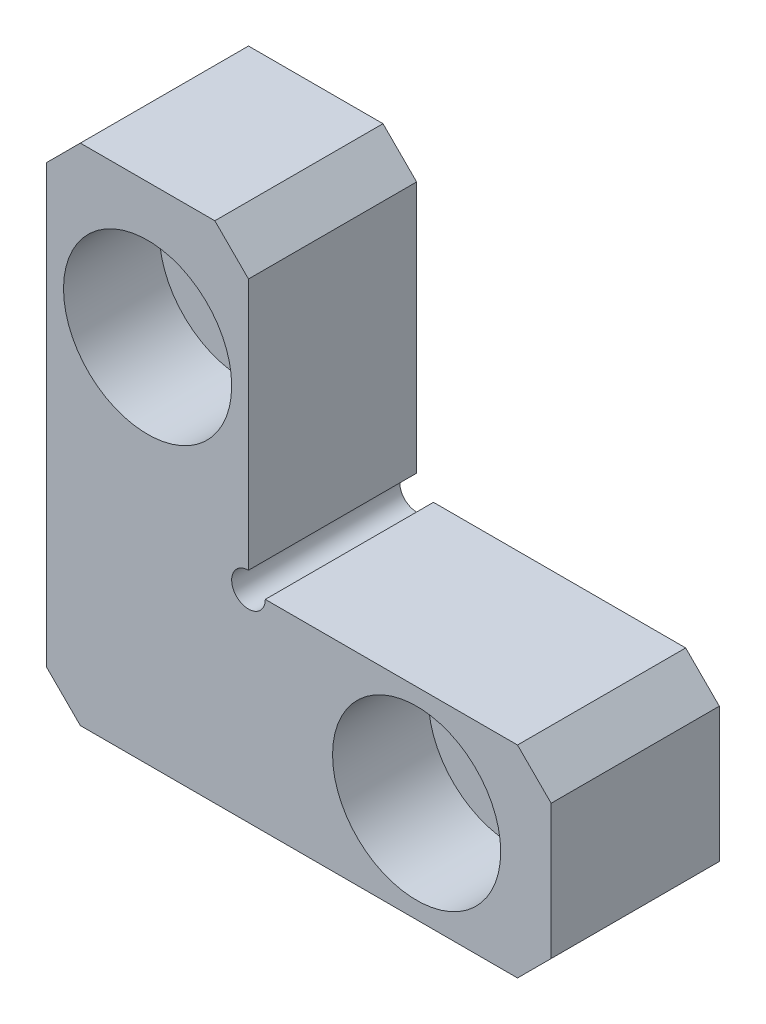
SolidWorks part; units mm, degrees
material "Q235-A"
ref_plane "前视基准面" through (0, 0, 0) normal (0, 0, 1) x (1, 0, 0)
ref_plane "上视基准面" through (0, 0, 0) normal (0, 1, 0) x (1, 0, 0)
ref_plane "右视基准面" through (0, 0, 0) normal (1, 0, 0) x (0, 0, -1)
sketch "草图1" plane through (0, 0, 0) normal (0, 0, 1) x (1, 0, 0)
  line L0 (0, 0) -> (0, 30)
  line L1 (0, 30) -> (12, 30)
  line L2 (12, 30) -> (12, 12)
  line L3 (12, 12) -> (30, 12)
  line L4 (30, 12) -> (30, 0)
  line L5 (30, 0) -> (0, 0)
  dimension "D1" = 30
  dimension "D2" = 30
  dimension "D3" = 12
  dimension "D4" = 12
extrude "凸台-拉伸1" add sketch "草图1" along normal mid plane 10
hole_wizard "打孔尺寸(%根据)内六角圆柱头螺钉的类型1" positions "草图4" profile "草图3" counterbore size "M5" standard "GB" end condition through all
sketch "草图4" plane through (0, 0, 5) normal (0, 0, 1) x (1, 0, 0)
  line L0 (0, 30) -> (0, 0) construction
  line L1 (0, 0) -> (30, 0) construction
  line L2 (12, 30) -> (0, 30) construction
  line L3 (30, 0) -> (30, 12) construction
  point P0 (6, 22)
  point P2 (22, 6)
  dimension "D1" = 6
  dimension "D2" = 6
  dimension "D3" = 8
  dimension "D4" = 8
sketch "草图3" plane through (6, 22, 5) normal (1, 0, 0) x (0, -1, 0)
  line L0 (0, 0) -> (0, 10)
  line L1 (0, 10) -> (2.75, 10)
  line L3 (2.75, 10) -> (2.75, 5.7)
  line L4 (2.75, 5.7) -> (5, 5.7)
  line L5 (5, 5.7) -> (5, 0)
  line L7 (5, 0) -> (0, 0)
  line L11 (0, -6.35) -> (0, 107.95) construction
  dimension "通孔孔直径" = 5.5
  dimension "通孔孔深度" = 10
  dimension "柱形沉头孔直径" = 10
  dimension "柱形沉头孔深度" = 5.7
chamfer "倒角1" distance 2 angle 45 5 edges at (0, 0, 0) (30, 0, 0) (30, 12, 0) (12, 30, 0) (0, 30, 0)
sketch "草图5" plane through (0, 0, 5) normal (0, 0, 1) x (1, 0, 0)
  circle A0 centre (12, 12) radius 1
  dimension "D1" = 2
extrude "切除-拉伸1" cut sketch "草图5" against normal through all
